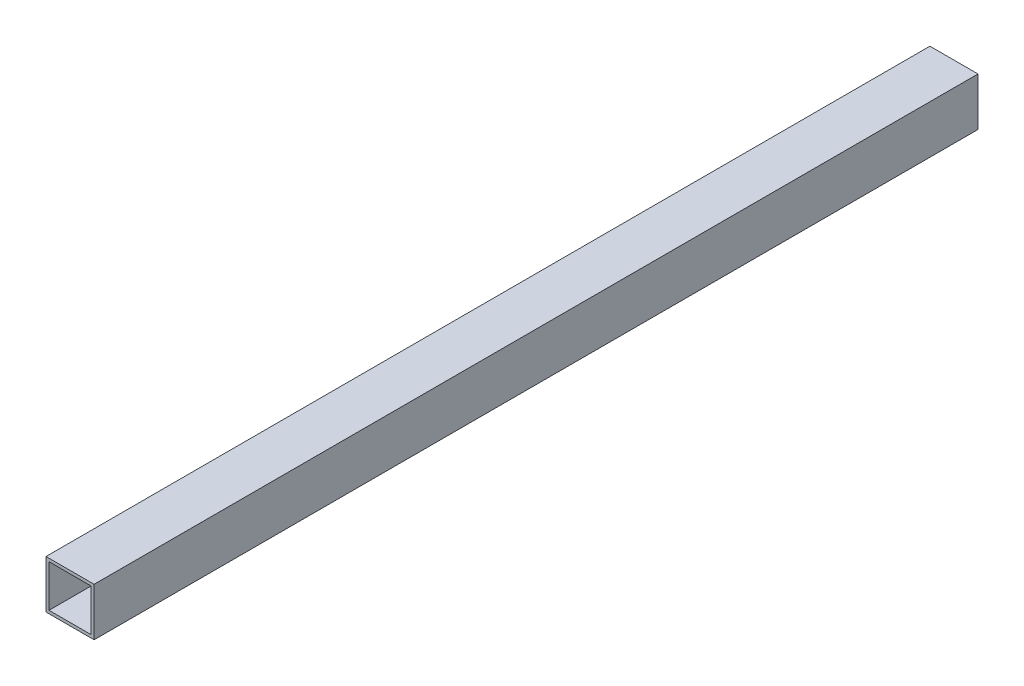
SolidWorks part; units mm, degrees
ref_plane "Alzado" through (0, 0, 0) normal (0, 0, 1) x (1, 0, 0)
ref_plane "Planta" through (0, 0, 0) normal (0, 1, 0) x (1, 0, 0)
ref_plane "Vista lateral" through (0, 0, 0) normal (1, 0, 0) x (0, 0, -1)
sketch "Croquis1" plane through (0, 0, 0) normal (0, 0, 1) x (1, 0, 0)
  line L0 (4.7625, -4.7625) -> (71.4375, -4.7625)
  line L1 (0, 0) -> (76.2, 0)
  line L2 (0, 0) -> (0, -76.2)
  line L3 (0, -76.2) -> (76.2, -76.2)
  line L4 (76.2, 0) -> (76.2, -76.2)
  line L5 (71.4375, -4.7625) -> (71.4375, -71.4375)
  line L6 (4.7625, -71.4375) -> (71.4375, -71.4375)
  line L7 (4.7625, -4.7625) -> (4.7625, -71.4375)
  dimension "D1" = 76.2
  dimension "D2" = 76.2
  dimension "D3" = 4.7625
extrude "Saliente-Extruir1" add sketch "Croquis1" along normal blind 1400
